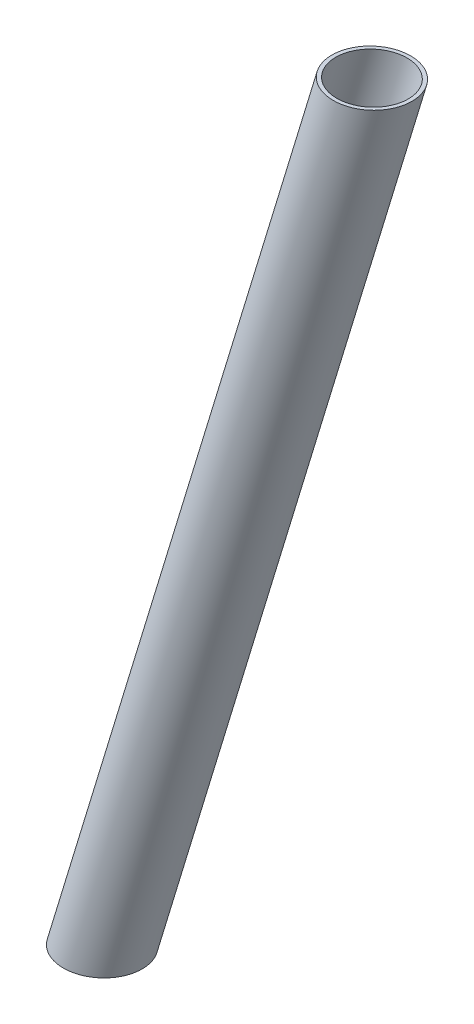
SolidWorks part; units mm, degrees
material "Thornel Mat VMA"
ref_plane "Front Plane" through (0, 0, 0) normal (0, 0, 1) x (1, 0, 0)
ref_plane "Top Plane" through (0, 0, 0) normal (0, 1, 0) x (1, 0, 0)
ref_plane "Right Plane" through (0, 0, 0) normal (1, 0, 0) x (0, 0, -1)
ref_plane "Plane1" through (0, 176.98, 0) normal (0, 1, 0) x (1, 0, 0)
sketch "Sketch4" plane through (0, 176.98, 0) normal (0, 1, 0) x (1, 0, 0)
  ellipse E1 centre (61.8631, 0) end of major axis (69.8631, 0) minor radius 7.72
sketch "Sketch7" plane through (0, 176.98, 0) normal (0, 1, 0) x (1, 0, 0)
  ellipse E0 centre (61.8631, 0) end of major axis (54.63, -0.0121) minor radius 7
sketch "Sketch10" plane through (0, 0, 0) normal (0, 1, 0) x (1, 0, 0)
  ellipse E1 centre (7.9883, 0) end of major axis (-0.0117, 0) minor radius 7.72
sketch "Sketch12" plane through (0, 0, 0) normal (0, 0, 1) x (1, 0, 0)
  line L0 (61.8631, 176.98) -> (7.9883, 0)
loft "Loft1" add profiles "Sketch4", "Sketch10"
sweep "Cut-Sweep1" cut profiles "Sketch7" path "Sketch12"
